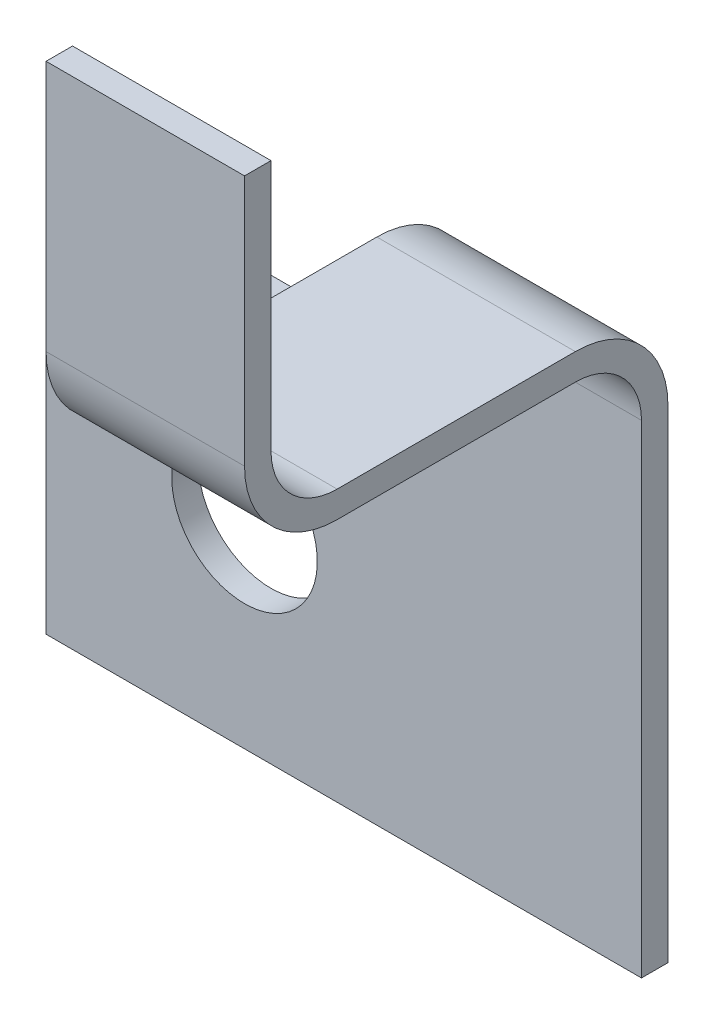
SolidWorks part; units mm, degrees
ref_plane "Front Plane" through (0, 0, 0) normal (0, 0, 1) x (1, 0, 0)
ref_plane "Top Plane" through (0, 0, 0) normal (0, 1, 0) x (1, 0, 0)
ref_plane "Right Plane" through (0, 0, 0) normal (1, 0, 0) x (0, 0, -1)
ref_plane "Plane1" through (28, 0, 0) normal (1, 0, 0) x (0, 0, -1)
sketch "Sketch1" plane through (28, 0, 0) normal (1, 0, 0) x (0, 0, -1)
  line L0 (-25.8, -229.284) -> (-25.8, -256.284)
  line L1 (-25.8, -256.284) -> (-13, -256.284)
  line L2 (-13, -256.284) -> (-13, -229.284)
  line L3 (-13, -229.284) -> (-25.8, -229.284)
extrude "Boss-Extrude1" add sketch "Sketch1" against normal blind 6
sketch "Sketch2" plane through (28, 0, 0) normal (1, 0, 0) x (0, 0, -1)
  line L0 (-13.8, -256.284) -> (-13.8, -239.684)
  line L1 (-13.8, -239.684) -> (-25.8, -239.684)
  line L2 (-25.8, -239.684) -> (-25.8, -256.284)
  line L3 (-25.8, -256.284) -> (-13.8, -256.284)
extrude "Cut-Extrude1" cut sketch "Sketch2" against normal through all
sketch "Sketch3" plane through (22, 0, 0) normal (-1, 0, 0) x (0, 0, 1)
  line L0 (13.8, -244.284) -> (13.8, -256.284)
  line L1 (13.8, -256.284) -> (13, -256.284)
  line L2 (13, -256.284) -> (13, -244.284)
  line L3 (13, -244.284) -> (13.8, -244.284)
extrude "Boss-Extrude2" add sketch "Sketch3" along normal blind 12
sketch "Sketch4" plane through (22, 0, 0) normal (-1, 0, 0) x (0, 0, 1)
  line L0 (13, -238.884) -> (25, -238.884)
  line L1 (25, -238.884) -> (25, -229.284)
  line L2 (25, -229.284) -> (13, -229.284)
  line L3 (13, -229.284) -> (13, -238.884)
extrude "Cut-Extrude2" cut sketch "Sketch4" against normal through all
hole_wizard "Hole1" positions "Sketch6" profile "Sketch5" legacy
sketch "Sketch6" plane through (0, 0, 13) normal (0, 0, -1) x (-1, 0, 0)
  point P0 (-16, -250.284)
sketch "Sketch5" plane through (16, -250.284, 13) normal (1, 0, 0) x (0, 1, 0)
  line L0 (0, 0) -> (0, 12.8)
  line L1 (0, 12.8) -> (2.2, 12.8)
  line L2 (2.2, 12.8) -> (2.2, 0)
  line L3 (2.2, 0) -> (0, 0)
  line L4 (0, 110) -> (0, -10) construction
  dimension "Diameter" = 4.4
  dimension "Depth" = 12.8
fillet "Fillet1" radius 2 1 edges at (25, -239.684, 13.8)
fillet "Fillet2" radius 2 1 edges at (25, -238.884, 25)
fillet "Fillet3" radius 2.8 1 edges at (25, -239.684, 25.8)
fillet "Fillet4" radius 2.8 1 edges at (25, -238.884, 13)
